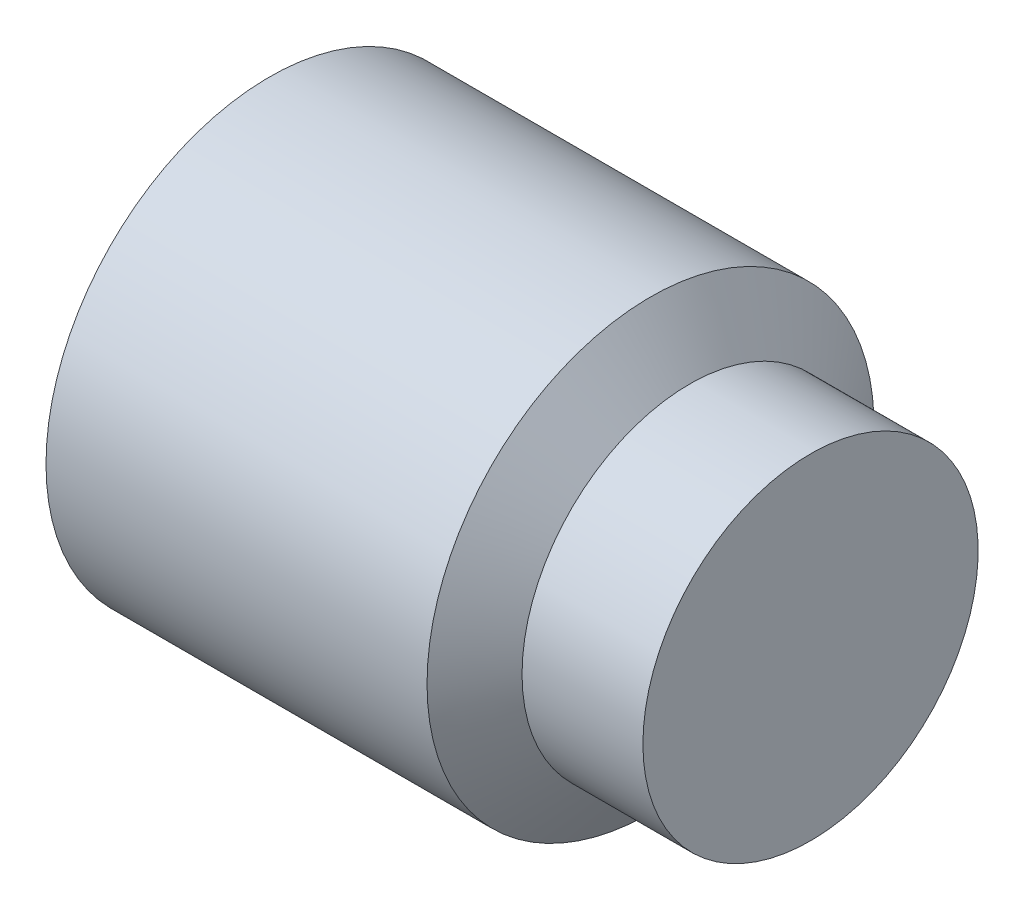
SolidWorks part; units mm, degrees
revolve "BaseBody" add sketch "BodySke" angle 360 about L5
sketch "BodySke" plane through (0, 0, 0) normal (0, 0, 1) x (1, 0, 0)
  line L0 (0, 0) -> (0, 10.352)
  line L1 (0, 10.352) -> (0.9515, 12)
  line L2 (0.9515, 12) -> (21.4094, 12)
  line L3 (21.4094, 12) -> (23.51, 9)
  line L4 (30, 0) -> (0, 0)
  line L5 (-12.7, 0) -> (88.9, 0) construction
  line L6 (23.51, 9) -> (30, 9)
  line L7 (30, 9) -> (30, 0)
  line L8 (0, -10.352) -> (0.9515, -12) construction
  line L9 (23.51, -9) -> (30, -9) construction
  line L10 (3, 15.875) -> (3, -3.175) construction
  dimension "Diameter" = 24
  dimension "Drive_ch_ang" = 60
  dimension "Minor_dia" = 20.704
  dimension "Dog_dia" = 18
  dimension "Dog_len" = 6.49
  dimension "Length" = 30
  dimension "Advance" = 3
  dimension "D1" = 35
cosmetic thread "ThreadCosmetic" [suppressed] parameters "Thread_minor"=20.704
ref_plane "Plane1" through (0, 0, 0) normal (0, 0, 1) x (1, 0, 0)
ref_plane "Plane2" through (0, 0, 0) normal (0, 1, 0) x (1, 0, 0)
ref_plane "Plane3" through (0, 0, 0) normal (1, 0, 0) x (0, 0, -1)
sketch "Sketch2" plane through (0, 0, 0) normal (-1, 0, 0) x (0, 0, 1)
  line L0 (3.4641, 6) -> (-3.4641, 6)
  line L1 (-3.4641, 6) -> (-6.9282, 0)
  line L2 (3.4641, 6) -> (6.9282, 0)
  line L3 (3.4641, -6) -> (6.9282, 0)
  line L4 (3.4641, -6) -> (-3.4641, -6)
  line L5 (-3.4641, -6) -> (-6.9282, 0)
  dimension "Hex_size" = 12
  dimension "D2" = 6
  dimension "D3" = 6
extrude "Hex" cut sketch "Sketch2" against normal blind 12
sketch "Sketch4" plane through (0, 4.7709, -0.5249) normal (-1, 0, 0) x (0, 0, 1)
  line L0 (0.5249, -4.7709) -> (8.1959, -4.7709)
  line L1 (0.5249, -4.7709) -> (6.6732, -1.2211) construction
  line L2 (0.5249, -4.7709) -> (4.3604, 1.8724)
  line L3 (6.7899, -3.1774) -> (7.8687, -2.5545)
  line L4 (5.0374, -0.142) -> (6.1162, 0.4809)
  arc A0 (6.7899, -3.1774) -> (5.0374, -0.142) centre (0.5249, -4.7709) ccw
  arc A1 (8.1959, -4.7709) -> (7.8687, -2.5545) centre (0.5249, -4.7709) ccw
  arc A2 (4.3604, 1.8724) -> (6.1162, 0.4809) centre (0.5249, -4.7709) cw
  circle A3 centre (0.5249, -4.7709) radius 6.4645 construction
  circle A4 centre (0.5249, -4.7709) radius 7.671 construction
  dimension "Spline_n_dim" = 12.929
  dimension "Spline_m_dim" = 15.342
  dimension "D1" = 30
  dimension "Spline_a_dim" = 60
  dimension "Spline_p_dim" = 3.505
  dimension "D3" = 1.7525
extrude "Spline6" [suppressed] cut sketch "Sketch4" against normal blind 12
pattern_circular "CirPattern1" [suppressed] count 6 every 60 about axis through (-12.7, 0, 0) along (1, 0, 0)
sketch "Sketch5" plane through (0, 0.4822, 7.7588) normal (-1, 0, 0) x (0, 0, 1)
  line L0 (-7.7588, -0.4822) -> (-0.0878, -0.4822)
  line L1 (-7.7588, -0.4822) -> (-2.7387, 4.538) construction
  line L2 (-7.7588, -0.4822) -> (-7.7588, 7.1888)
  line L3 (-1.9485, 2.8497) -> (-1.2389, 3.5594)
  line L4 (-4.4269, 5.3281) -> (-3.7173, 6.0378)
  line L5 (-4.4269, 5.3281) -> (-1.9485, 2.8497)
  arc A1 (-0.0878, -0.4822) -> (-1.2389, 3.5594) centre (-7.7588, -0.4822) ccw
  arc A2 (-7.7588, 7.1888) -> (-3.7173, 6.0378) centre (-7.7588, -0.4822) cw
  circle A3 centre (-7.7588, -0.4822) radius 6.4645 construction
  circle A4 centre (-7.7588, -0.4822) radius 7.671 construction
  dimension "Spline_n_dim" = 12.929
  dimension "Spline_m_dim" = 15.342
  dimension "Spline_p_dim" = 3.505
  dimension "D3" = 1.7525
  dimension "D1" = 45
  dimension "Spline_a_dim" = 90
extrude "Spline4" [suppressed] cut sketch "Sketch5" against normal blind 12
pattern_circular "CirPattern2" [suppressed] count 4 every 90 about axis through (-12.7, 0, 0) along (1, 0, 0)
sketch "ThdSchSke" plane through (0, 0, 0) normal (0, 0, 1) x (1, 0, 0)
  line L0 (0.9515, -10.352) -> (-0.2025, -12)
  line L1 (0.9515, -10.352) -> (2.1054, -12)
  line L2 (2.1054, -12) -> (2.1054, -15)
  line L3 (-3.175, 0) -> (5.1513, 0) construction
  line L4 (0.9515, 12) -> (0.9515, -12) construction
  line L5 (2.1054, -15) -> (-0.2025, -15)
  line L6 (-0.2025, -15) -> (-0.2025, -12)
  dimension "Thread_minor" = 20.704
  dimension "Diameter" = 24
revolve "ThreadSchematic" [suppressed] cut sketch "ThdSchSke" angle 360 about L3
pattern_linear "ThdSchPat" [suppressed]
equation "\"D2@Sketch2\" = \"Hex_size@Sketch2\" / 2"
equation "\"D3@Sketch2\" = \"Hex_size@Sketch2\" / 2"
equation "\"Thread_minor@ThreadCosmetic\" = \"Minor_dia@BodySke\""
equation "\"D1@Sketch4\" = \"Spline_a_dim@Sketch4\" / 2"
equation "\"D3@Sketch4\" = \"Spline_p_dim@Sketch4\" / 2"
equation "\"D2@CirPattern1\" = \"Spline_a_dim@Sketch4\""
equation "\"Num_teeth@CirPattern1\" = 360 / \"D2@CirPattern1\""
equation "\"Spline_a_dim@Sketch5\" = 90"
equation "\"Spline_p_dim@Sketch5\" = \"Spline_p_dim@Sketch4\""
equation "\"Spline_m_dim@Sketch5\" = \"Spline_m_dim@Sketch4\""
equation "\"Spline_n_dim@Sketch5\" = \"Spline_n_dim@Sketch4\""
equation "\"D1@Sketch5\" = \"Spline_a_dim@Sketch5\" / 2"
equation "\"D3@Sketch5\" = \"Spline_p_dim@Sketch5\" / 2"
equation "\"Key_eng@Spline4\" = \"Key_eng@Spline6\""
equation "\"Thread_minor@ThdSchSke\" = \"Thread_minor@ThreadCosmetic\""
equation "\"Diameter@ThdSchSke\" = \"Diameter@BodySke\""
equation "\"Overcut@ThdSchSke\" = \"Diameter@BodySke\" * 1.25"
equation "\"Num_threads@ThdSchPat\" = int( (\"Length@BodySke\" - ( ( ( \"Diameter@BodySke\" - \"Minor_dia@BodySke\" ) * 0.5 ) / tan( \"Drive_ch_ang@BodySke\" * 0.017453292 ) ) - \"Dog_len@BodySke\" ) / \"Advance@BodySke\" + 0.999 )  + 1"
equation "\"Advance@ThdSchPat\" = (\"Length@BodySke\" - ( ( ( \"Diameter@BodySke\" - \"Minor_dia@BodySke\" ) * 0.5 ) / tan( \"Drive_ch_ang@BodySke\" * 0.017453292 ) ) - \"Dog_len@BodySke\" ) /  (\"Num_threads@ThdSchPat\" - 1) 'relax it"
equation "\"Num_threads@ThdSchPat\" = \"Num_threads@ThdSchPat\" - sgn( \"Num_threads@ThdSchPat\" - 1) '---chamfered tips only---"
